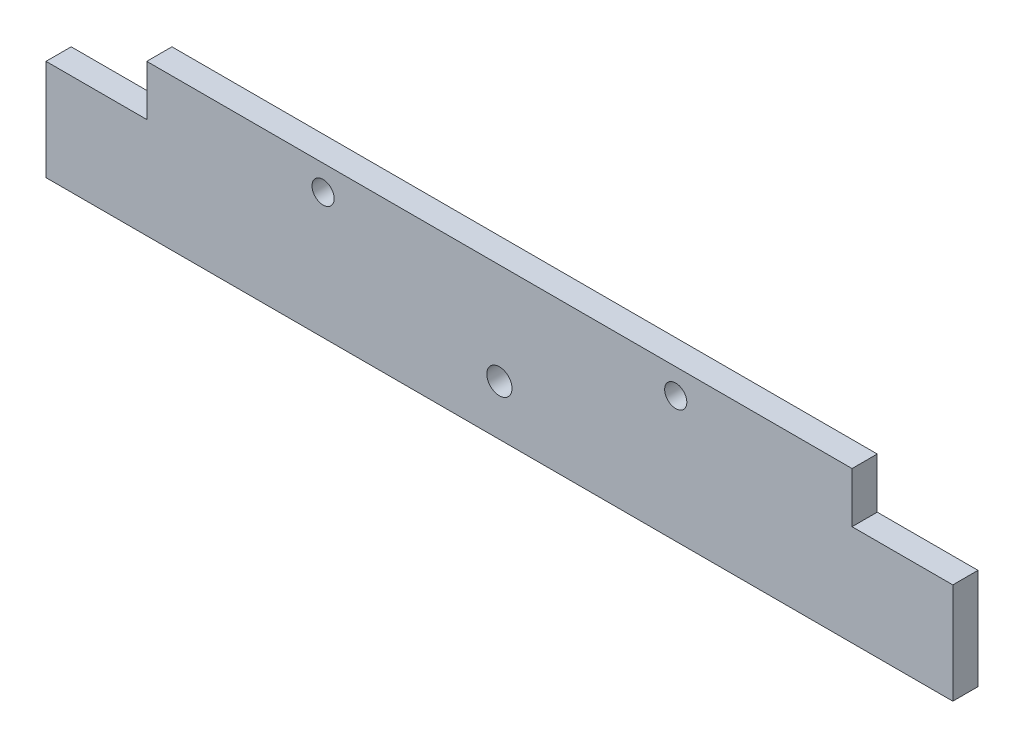
SolidWorks part; units mm, degrees
material "ABS"
ref_plane "Płaszczyzna przednia" through (0, 0, 0) normal (0, 0, 1) x (1, 0, 0)
ref_plane "Płaszczyzna górna" through (0, 0, 0) normal (0, 1, 0) x (1, 0, 0)
ref_plane "Płaszczyzna prawa" through (0, 0, 0) normal (1, 0, 0) x (0, 0, -1)
sketch "Szkic1" plane through (0, 0, 0) normal (0, 0, 1) x (1, 0, 0)
  line L0 (0, -10) -> (-20, -10)
  line L2 (0, -10) -> (0, 0)
  line L3 (0, 0) -> (140, 0)
  line L4 (140, -10) -> (140, 0)
  line L7 (-20, -10) -> (-20, -30)
  line L8 (-20, -30) -> (160, -30)
  line L9 (160, -30) -> (160, -10)
  line L10 (160, -10) -> (140, -10)
  point P0 (0, 0)
  dimension "D1" = 180
  dimension "D2" = 30
  dimension "D3" = 10
  dimension "D4" = 20
  dimension "D5" = 20
extrude "Dodanie-wyciągnięcie1" add sketch "Szkic1" along normal blind 5
sketch "Szkic2" plane through (0, 0, 5) normal (0, 0, 1) x (1, 0, 0)
  line L0 (140, 0) -> (0, 0) construction
  line L1 (0, 0) -> (0, -10) construction
  line L2 (140, -10) -> (140, 0) construction
  circle A0 centre (35, -5) radius 2.2
  circle A2 centre (105, -5) radius 2.2
  dimension "D1" = 5
  dimension "D4" = 4.4
  dimension "D2" = 35
  dimension "D3" = 35
extrude "Wytnij-wyciągnięcie1" cut sketch "Szkic2" against normal blind 10
sketch "Szkic6" plane through (0, 0, 5) normal (0, 0, 1) x (1, 0, 0)
  line L0 (-20, -30) -> (160, -30) construction
  line L1 (160, -30) -> (160, -10) construction
  circle A0 centre (70, -20) radius 2.5
  dimension "D1" = 10
  dimension "D2" = 5
  dimension "D3" = 90
extrude "Wytnij-wyciągnięcie3" cut sketch "Szkic6" against normal through all
